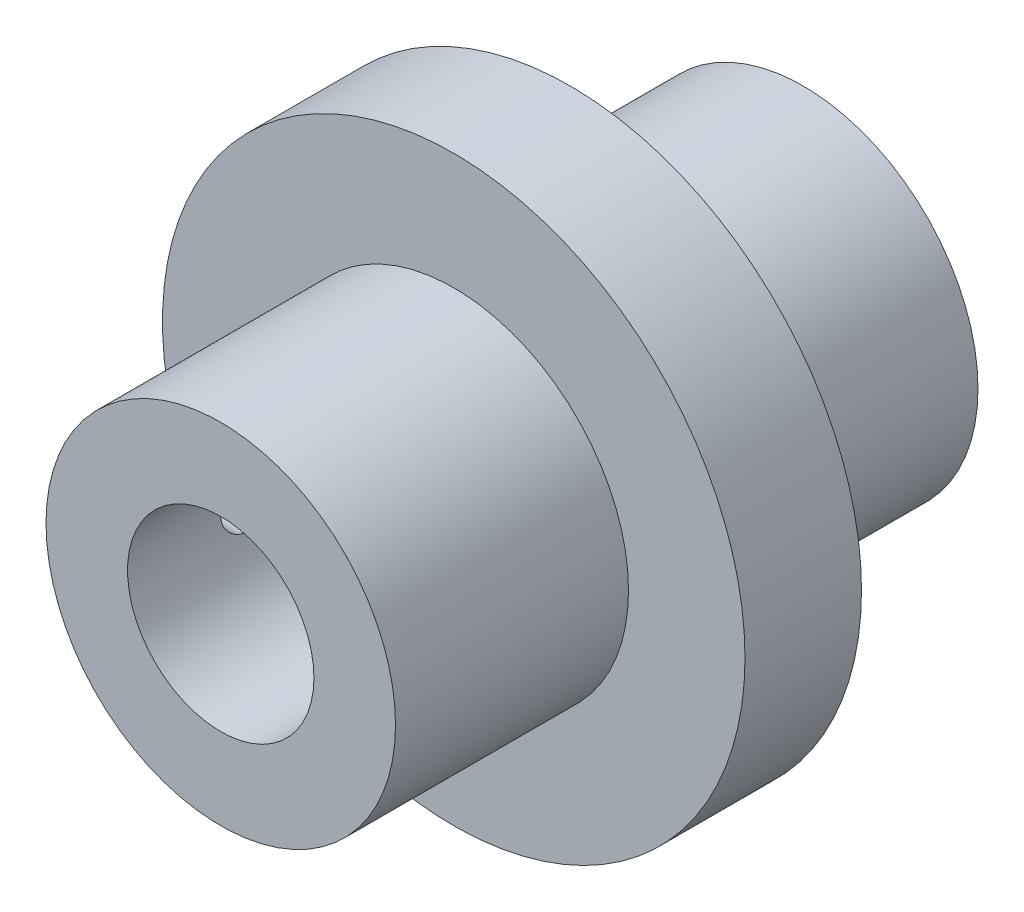
SolidWorks part; units mm, degrees
ref_plane "Front Plane" through (0, 0, 0) normal (0, 0, 1) x (1, 0, 0)
ref_plane "Top Plane" through (0, 0, 0) normal (0, 1, 0) x (1, 0, 0)
ref_plane "Right Plane" through (0, 0, 0) normal (1, 0, 0) x (0, 0, -1)
sketch "Sketch1" plane through (0, 0, 0) normal (0, 0, 1) x (1, 0, 0)
  circle A0 centre (0, 0) radius 4
  circle A1 centre (0, 0) radius 7.5
  dimension "D1" = 8
  dimension "D2" = 15
extrude "Boss-Extrude1" add sketch "Sketch1" along normal blind 10 contours A1
sketch "Sketch3" plane through (0, 0, 10) normal (0, 0, 1) x (1, 0, 0)
  circle A0 centre (0, 0) radius 4
  circle A1 centre (0, 0) radius 12.5
  dimension "D1" = 25
extrude "Boss-Extrude2" add sketch "Sketch3" along normal blind 5
sketch "Sketch4" plane through (0, 0, 15) normal (0, 0, 1) x (1, 0, 0)
  circle A0 centre (0, 0) radius 4
  circle A1 centre (0, 0) radius 7.5
  dimension "D1" = 8
  dimension "D2" = 15
extrude "Boss-Extrude3" add sketch "Sketch4" along normal blind 10
sketch "Sketch5" plane through (0, 0, 0) normal (1, 0, 0) x (0, 0, -1)
  line L0 (0, 0) -> (-20, 0) construction
  circle A0 centre (-20, 0) radius 1
  dimension "D2" = 2
  dimension "D1" = 20
extrude "Cut-Extrude1" cut sketch "Sketch5" against normal blind 10
